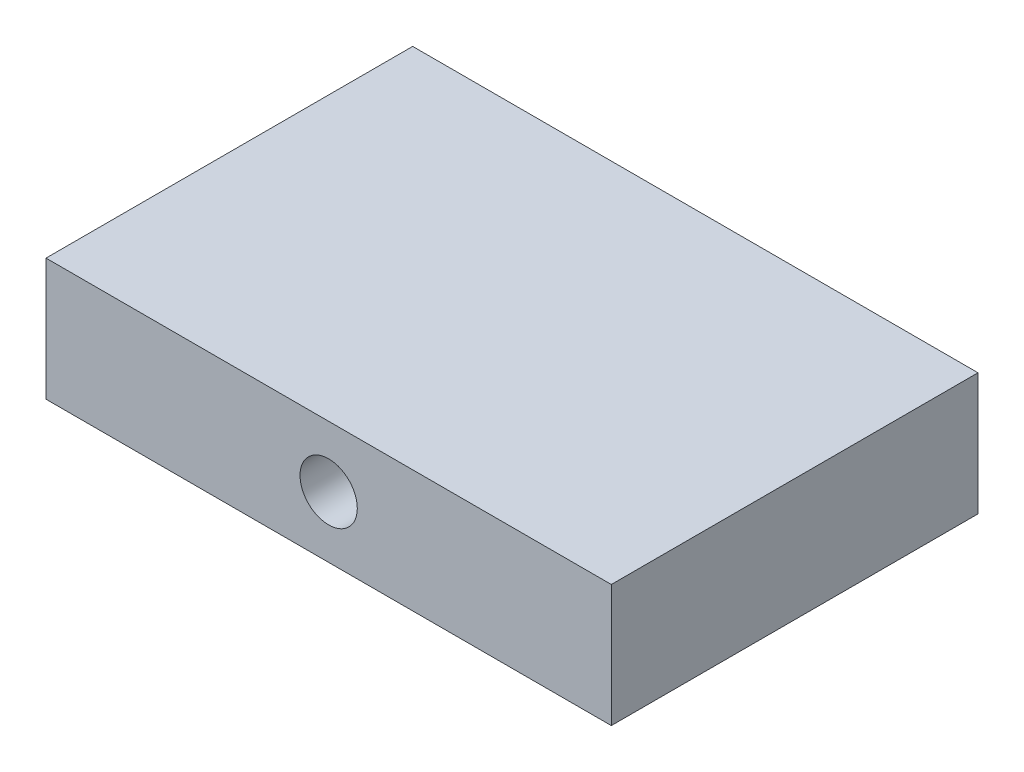
SolidWorks part; units mm, degrees
ref_plane "Front Plane" through (0, 0, 0) normal (0, 0, 1) x (1, 0, 0)
ref_plane "Top Plane" through (0, 0, 0) normal (0, 1, 0) x (1, 0, 0)
ref_plane "Right Plane" through (0, 0, 0) normal (1, 0, 0) x (0, 0, -1)
sketch "Sketch2" plane through (0, 0, 0) normal (0, 1, 0) x (1, 0, 0)
  line L1 (37, -24) -> (-37, -24)
  line L2 (37, -24) -> (37, 24)
  line L3 (37, 24) -> (-37, 24)
  line L4 (-37, -24) -> (-37, 24)
  line L5 (37, -24) -> (-37, 24) construction
  line L6 (37, 24) -> (-37, -24) construction
  point P0 (0, 0)
  dimension "D1" = 74
  dimension "D2" = 48
extrude "Boss-Extrude1" add sketch "Sketch2" along normal blind 16
sketch "Sketch3" plane through (0, 0, 24) normal (0, 0, 1) x (1, 0, 0)
  line L1 (-37, 16) -> (-37, 0) construction
  circle A0 centre (0, 8) radius 3.75
  point P2 (0, 0)
  point P3 (0, 0)
  point P4 (0, 0)
  point P5 (0, 0)
  point P6 (0, 0)
  point P9 (0, 8)
  point P11 (0, 0)
  point P12 (0, 0)
  point P13 (0, 0)
  point P14 (-37, 8)
  point P15 (0, 0)
  point P16 (0, 8)
  point P17 (0, 0)
  dimension "D1" = 7.5
extrude "Cut-Extrude1" cut sketch "Sketch3" against normal through all
